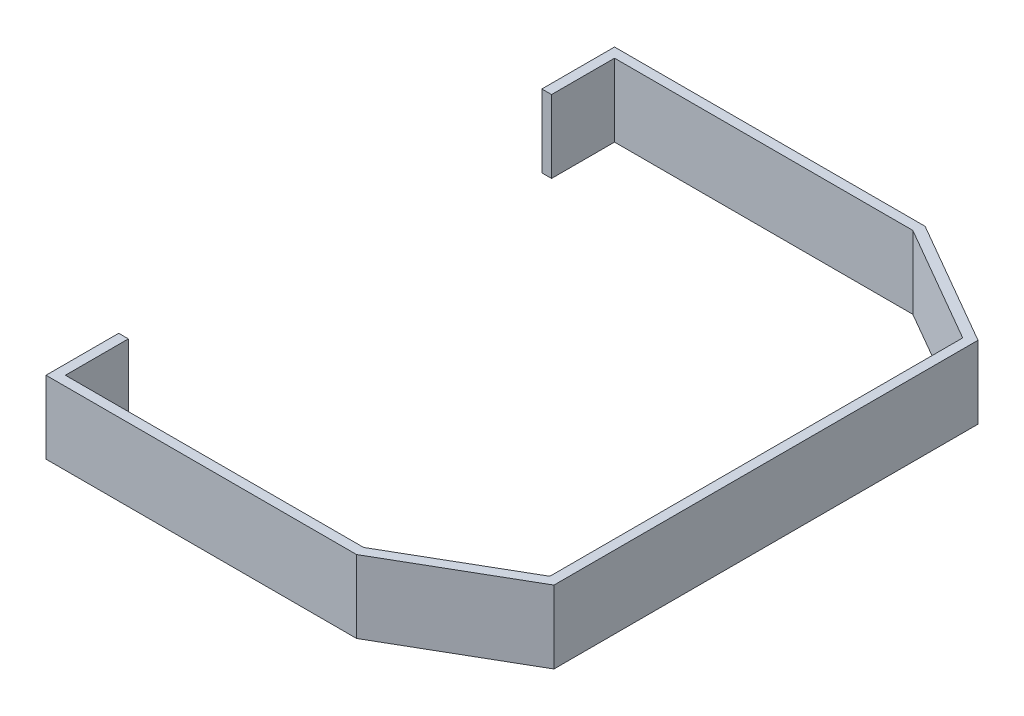
SolidWorks part; units mm, degrees
ref_plane "Front Plane" through (0, 0, 0) normal (0, 0, 1) x (1, 0, 0)
ref_plane "Top Plane" through (0, 0, 0) normal (0, 1, 0) x (1, 0, 0)
ref_plane "Right Plane" through (0, 0, 0) normal (1, 0, 0) x (0, 0, -1)
sketch "Sketch6" plane through (0, 0, 0) normal (0, 1, 0) x (1, 0, 0)
  line L0 (-142.3198, -87.5) -> (-142.3198, 87.5) construction
  line L1 (-142.3198, 87.5) -> (-90.67, 117.32) construction
  line L2 (-90.67, 117.32) -> (-37.5, 117.32) construction
  line L3 (-37.5, 117.32) -> (-37.5, 87.32) construction
  line L4 (-37.5, 87.32) -> (37.5, 87.32) construction
  line L5 (37.5, 87.32) -> (37.5, 117.32) construction
  line L6 (37.5, 117.32) -> (90.67, 117.32) construction
  line L7 (90.67, 117.32) -> (142.3198, 87.5) construction
  line L8 (142.3198, 87.5) -> (142.3198, -87.5) construction
  line L9 (-142.3198, 0) -> (142.3198, 0) construction
  line L10 (90.67, -117.32) -> (142.3198, -87.5) construction
  line L11 (37.5, -117.32) -> (90.67, -117.32) construction
  line L12 (-37.5, -87.32) -> (37.5, -87.32) construction
  line L13 (-37.5, -117.32) -> (-37.5, -87.32) construction
  line L14 (-90.67, -117.32) -> (-37.5, -117.32) construction
  line L15 (-142.3198, -87.5) -> (-90.67, -117.32) construction
  line L16 (37.5, -87.32) -> (37.5, -117.32) construction
  line L39 (0, 117.32) -> (90.67, 117.32)
  line L40 (90.67, 117.32) -> (142.3198, 87.5)
  line L41 (142.3198, 87.5) -> (142.3198, -87.5)
  line L42 (142.3198, -87.5) -> (90.67, -117.32)
  line L43 (90.67, -117.32) -> (0, -117.32)
  line L44 (0, 117.32) -> (0, -117.32) construction
  line L45 (0, 117.32) -> (-37.5, 117.32)
  line L47 (-37.5, -117.32) -> (0, -117.32)
  line L48 (-33.5, -113.32) -> (0, -113.32)
  line L49 (89.5982, -113.32) -> (0, -113.32)
  line L50 (138.3198, -85.1906) -> (89.5982, -113.32)
  line L51 (138.3198, 85.1906) -> (138.3198, -85.1906)
  line L52 (89.5982, 113.32) -> (138.3198, 85.1906)
  line L53 (0, 113.32) -> (89.5982, 113.32)
  line L54 (0, 113.32) -> (-33.5, 113.32)
  line L56 (-37.5, 117.32) -> (-37.5, -117.32) construction
  line L57 (-33.5, 113.32) -> (-33.5, -113.32) construction
  line L58 (-37.5, 117.32) -> (-37.5, 87.32)
  line L59 (-37.5, 87.32) -> (-33.5, 87.32)
  line L60 (-33.5, 87.32) -> (-33.5, 113.32)
  line L61 (-37.5, -117.32) -> (-37.5, -87.32)
  line L62 (-37.5, -87.32) -> (-33.5, -87.32)
  line L63 (-33.5, -87.32) -> (-33.5, -113.32)
  point P6 (0, 87.32)
  point P11 (0, 0)
  dimension "D1" = 30
  dimension "D2" = 75
  dimension "D3" = 53.17
  dimension "D4" = 87.5
  dimension "D5" = 59.64
  dimension "D6" = 120
  dimension "D7" = 4
extrude "Boss-Extrude1" add sketch "Sketch6" along normal blind 30
